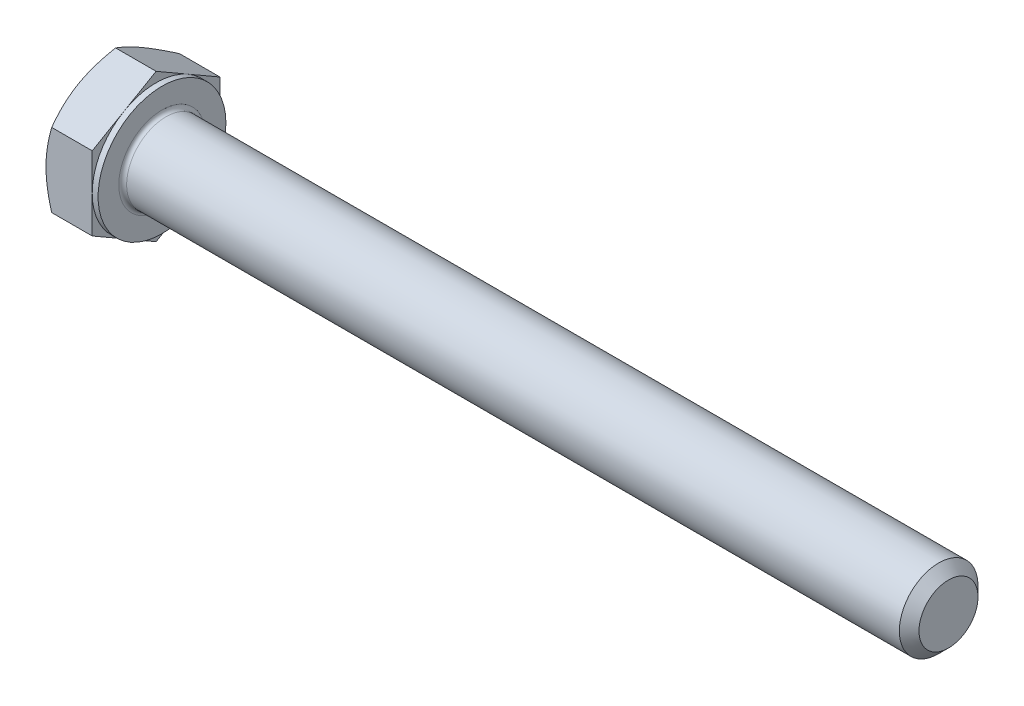
SolidWorks part; units mm, degrees
extrude "基体-拉伸" add sketch "草图1" along normal blind 5.3
sketch "草图1" plane through (0, 0, 0) normal (1, 0, 0) x (0, 0, -1)
  line L0 (6.5, 3.7528) -> (6.5, -3.7528)
  line L1 (-6.5, 3.7528) -> (-6.5, -3.7528)
  line L2 (6.5, -3.7528) -> (0, -7.5056)
  line L3 (0, -7.5056) -> (-6.5, -3.7528)
  line L4 (6.5, 3.7528) -> (0, 7.5056)
  line L5 (0, 7.5056) -> (-6.5, 3.7528)
  dimension "s" = 13
  dimension "D2" = 120
  dimension "D3" = 6.5
  dimension "D4" = 6.5
  dimension "D5" = 6.5
revolve "切除-旋转1" cut sketch "草图3" angle 360 about L6
sketch "草图3" plane through (0, 0, 0) normal (0, 0, 1) x (1, 0, 0)
  line L0 (0, 6.5) -> (3.4673, 12.5056)
  line L1 (0, 7.5056) -> (0, 3.7528) construction
  line L2 (3.4673, 12.5056) -> (3.4673, 17.5056)
  line L3 (3.4673, 17.5056) -> (-10, 17.5056)
  line L4 (-10, 17.5056) -> (-10, 6.5)
  line L5 (-10, 6.5) -> (0, 6.5)
  line L6 (0, 0) -> (99.06, 0) construction
  line L7 (5.3, 7.5056) -> (0, 7.5056) construction
  dimension "D1" = 6.5
  dimension "D2" = 5
  dimension "D3" = 10
  dimension "D4" = 5
  dimension "Head_ch_ang" = 30
material "3.6级"
ref_plane "前视" through (0, 0, 0) normal (0, 0, 1) x (1, 0, 0)
ref_plane "上视" through (0, 0, 0) normal (0, 1, 0) x (1, 0, 0)
ref_plane "右视" through (0, 0, 0) normal (1, 0, 0) x (0, 0, -1)
sketch "草图2" plane through (0, 0, 0) normal (0, 0, 1) x (1, 0, 0)
  line L0 (0, 3.7528) -> (0, -3.7528) construction
  line L1 (0, 0) -> (85.3, 0)
  line L2 (0, 0) -> (0, 4)
  line L3 (0, 4) -> (27.8072, 4)
  line L4 (85.3, 0) -> (85.3, 2.9175)
  line L5 (5.3, 7.5056) -> (5.3, 3.7528) construction
  line L7 (0, 0) -> (96.52, 0) construction
  line L8 (85.3, -2.9175) -> (27.8072, -4) construction
  line L9 (0, -4) -> (27.8072, -4) construction
  line L10 (6.55, 15.24) -> (6.55, -1.27) construction
  line L11 (63.3, 15.24) -> (63.3, -1.27) construction
  line L12 (5.3, 3.7528) -> (5.3, -3.7528) construction
  line L13 (27.8072, 4) -> (85.3, 4)
  line L14 (85.3, 4) -> (85.3, 2.9175)
revolve "凸台-旋转1" add sketch "草图2" angle 360 about L7
cosmetic thread "螺旋线1" parameters "Thread_length"=22, "Thread_minor"=5.835
sketch "草图5" plane through (0, 0, 0) normal (0, 0, 1) x (1, 0, 0)
  line L0 (5.3, 6.5) -> (1.8327, 12.5056)
  line L1 (5.3, 7.5056) -> (5.3, 3.7528) construction
  line L2 (1.8327, 12.5056) -> (1.8327, 17.5056)
  line L3 (1.8327, 17.5056) -> (11.8327, 17.5056)
  line L4 (11.8327, 17.5056) -> (11.8327, 6.5)
  line L5 (11.8327, 6.5) -> (5.3, 6.5)
  line L7 (5.3, 7.5056) -> (0.5806, 7.5056) construction
  line L8 (0, 0) -> (99.06, 0) construction
  line L9 (0, 0) -> (99.06, 0) construction
  dimension "D1" = 6.5
  dimension "D2" = 5
  dimension "D3" = 10
  dimension "D4" = 5
  dimension "Head_ch_ang" = 30
revolve "切除-旋转2" cut sketch "草图5" angle 360 about L8
sketch "草图4" plane through (0, 0, 0) normal (0, 0, 1) x (1, 0, 0)
  line L1 (5.3, 7.5056) -> (5.3, 3.7528) construction
  line L2 (5.3, 6.5) -> (4.7, 6.5)
  line L3 (5.3, 6.5) -> (5.3, 17.5056)
  line L4 (5.3, 17.5056) -> (4.7, 17.5056)
  line L5 (0, 0) -> (95.25, 0) construction
  line L6 (0, 0) -> (96.52, 0) construction
  line L7 (4.7, 6.5) -> (4.7, 17.5056)
  line L8 (4.7194, 7.5056) -> (0.5806, 7.5056) construction
  dimension "D2" = 10
  dimension "D1" = 13
revolve "切除-旋转3" cut sketch "草图4" angle 360 about L5
chamfer "倒角" distance 1 angle 45 1 edges at (85.3, 0, 4)
fillet "圆角" radius 0.4 1 edges at (5.3, 0, -4)
sketch "草图6" plane through (0, 0, 0) normal (0, 0, 1) x (1, 0, 0)
  line L0 (63.3, -2.9175) -> (62.675, -4)
  line L1 (63.3, -2.9175) -> (63.925, -4)
  line L2 (63.925, -4) -> (63.925, -5)
  line L3 (-3.175, 0) -> (5.1513, 0) construction
  line L5 (63.925, -5) -> (62.675, -5)
  line L6 (62.675, -5) -> (62.675, -4)
  dimension "Thread_minor" = 5.835
  dimension "Diameter" = 8
  dimension "Start" = 63.3
revolve "切除-旋转4" [suppressed] cut sketch "草图6" angle 360 about L3
pattern_linear "阵列(线性)1" [suppressed]
equation "\"D3@草图1\" = \"s@草图1\" / 2"
equation "\"D4@草图1\" = \"D3@草图1\""
equation "\"D5@草图1\" = \"D4@草图1\""
equation "\"Thread_minor@螺旋线1\" = \"Minor_dia@草图2\""
equation "\"D1@草图3\" = \"s@草图1\" / 2"
equation "\"D1@草图5\" = \"s@草图1\" / 2"
equation "\"Head_ch_ang@草图5\" = \"Head_ch_ang@草图3\""
equation "\"D1@草图4\" = \"s@草图1\""
equation "\"Thread_length@螺旋线1\" = ((sgn( (\"l@草图2\" - \"p@草图2\" ) - \"h@草图2\" )-1)*( (\"l@草图2\" - \"p@草图2\" ) - \"h@草图2\" ))/-2+ \"h@草图2\""
equation "\"Thread_minor@草图6\" = \"Minor_dia@草图2\""
equation "\"Diameter@草图6\" = \"m@草图2\""
equation "\"Overcut@草图6\" = \"m@草图2\" * 1.25"
equation "\"Start@草图6\" = \"k@基体-拉伸\" + \"l@草图2\" - \"Thread_length@螺旋线1\"  '---Non-countersunk---"
equation "\"Num_threads@阵列(线性)1\" = int( \"Thread_length@螺旋线1\" / \"p@草图2\" + 0.999 )  + 1"
equation "\"Advance@阵列(线性)1\" = \"Thread_length@螺旋线1\" /  (\"Num_threads@阵列(线性)1\" - 1) 'relax it"
equation "\"Num_threads@阵列(线性)1\" = \"Num_threads@阵列(线性)1\" - sgn( \"Num_threads@阵列(线性)1\" - 1) '---chamfered tips only---"
equation "\"Minor_dia@草图2\" = \"m@草图2\"-\"p@草图2\" * 1.732"
equation "\"D1@倒角\" = \"p@草图2\"*0.8"
